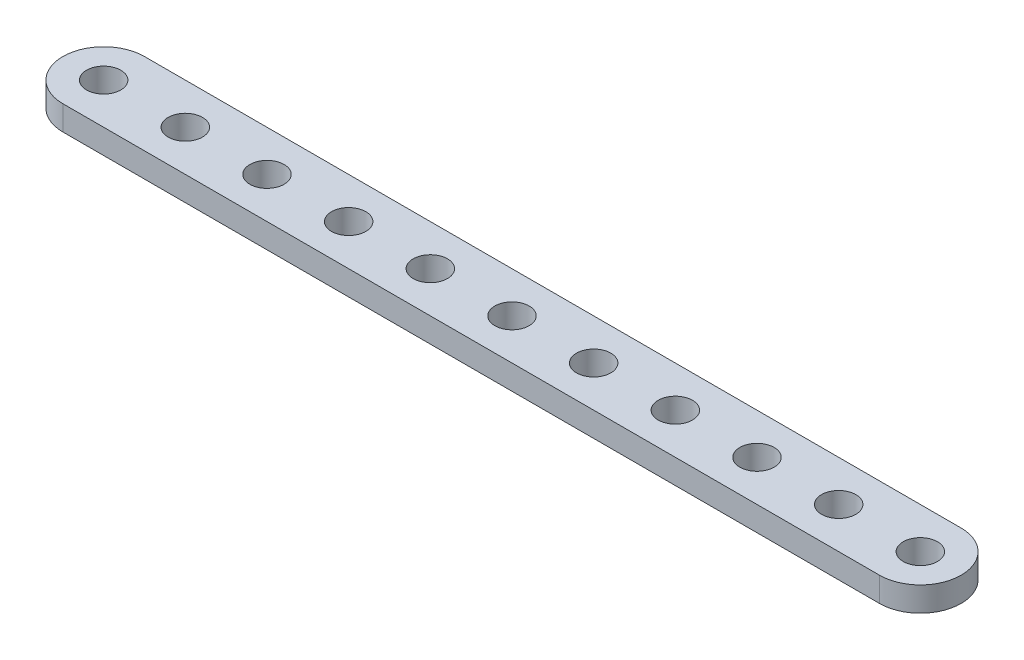
SolidWorks part; units mm, degrees
ref_plane "Front Plane" through (0, 0, 0) normal (0, 0, 1) x (1, 0, 0)
ref_plane "Top Plane" through (0, 0, 0) normal (0, 1, 0) x (1, 0, 0)
ref_plane "Right Plane" through (0, 0, 0) normal (1, 0, 0) x (0, 0, -1)
sketch "Sketch1" plane through (0, 0, 0) normal (0, 1, 0) x (1, 0, 0)
  line L0 (-50, 0) -> (50, 0) construction
  line L7 (-50, 5) -> (50, 5)
  line L10 (0, 22.95) -> (0, 25) construction
  line L11 (-50, -5) -> (50, -5)
  arc A5 (-50, 5) -> (-50, -5) centre (-50, 0) ccw
  arc A6 (50, -5) -> (50, 5) centre (50, 0) ccw
  circle A7 centre (50, 0) radius 2.1
  circle A8 centre (40, 0) radius 2.1
  circle A9 centre (30, 0) radius 2.1
  circle A10 centre (20, 0) radius 2.1
  circle A11 centre (10, 0) radius 2.1
  circle A12 centre (0, 0) radius 2.1
  circle A13 centre (-10, 0) radius 2.1
  circle A14 centre (-20, 0) radius 2.1
  circle A15 centre (-30, 0) radius 2.1
  circle A16 centre (-40, 0) radius 2.1
  circle A17 centre (-50, 0) radius 2.1
  point P2 (0, 0)
  dimension "D3" = 4.2
  dimension "D4" = 11
  dimension "D1" = 10
  dimension "D2" = 100
extrude "Boss-Extrude1" add sketch "Sketch1" along normal mid plane 3
